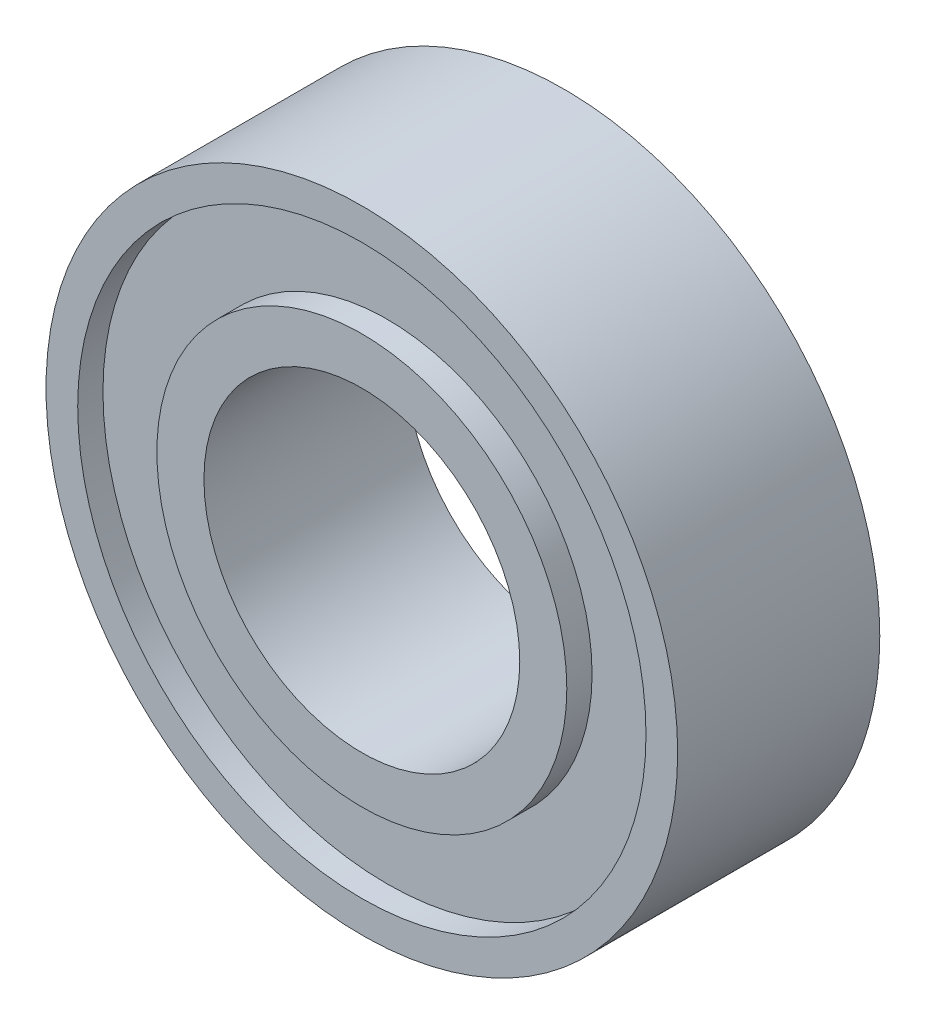
SolidWorks part; units mm, degrees
ref_plane "Front Plane" through (0, 0, 0) normal (0, 0, 1) x (1, 0, 0)
ref_plane "Top Plane" through (0, 0, 0) normal (0, 1, 0) x (1, 0, 0)
ref_plane "Right Plane" through (0, 0, 0) normal (1, 0, 0) x (0, 0, -1)
sketch "Sketch1" plane through (0, 0, 0) normal (0, 0, 1) x (1, 0, 0)
  circle A0 centre (0, 0) radius 12.5
  circle A1 centre (0, 0) radius 6.25
  dimension "D1" = 25
  dimension "D2" = 12.5
extrude "Boss-Extrude1" add sketch "Sketch1" along normal blind 8
sketch "Sketch2" plane through (0, 0, 8) normal (0, 0, 1) x (1, 0, 0)
  circle A0 centre (0, 0) radius 11.2464
  circle A1 centre (0, 0) radius 8.1125
extrude "Cut-Extrude1" cut sketch "Sketch2" against normal blind 1 contours A0 A1
ref_plane "Plane1" through (0, 0, 4) normal (0, 0, 1) x (1, 0, 0)
mirror "Mirror1" about plane through (0, 0, 4) normal (0, 0, 1) of "Cut-Extrude1"
